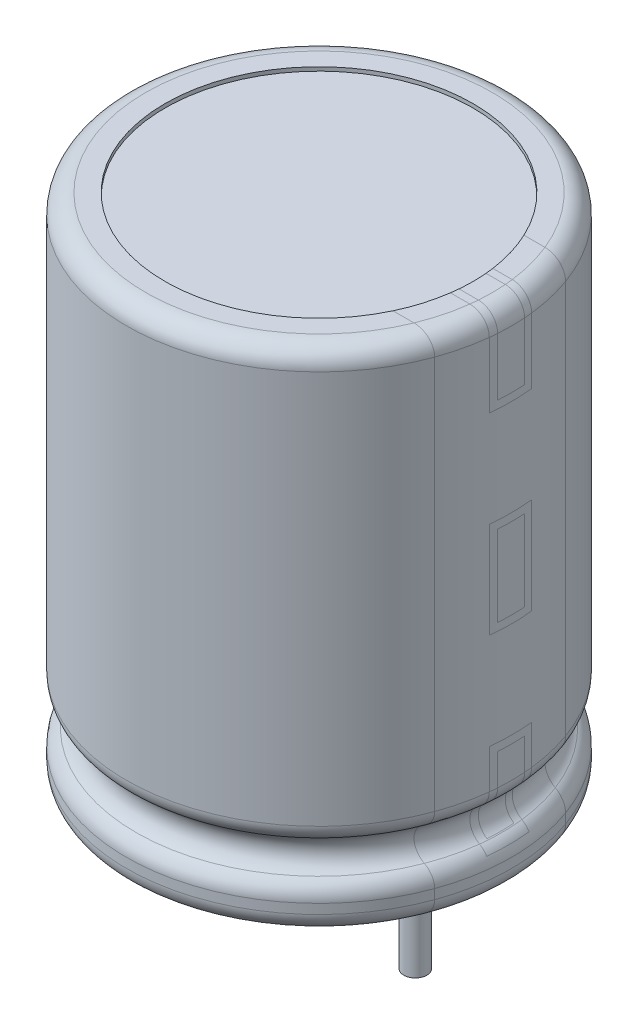
SolidWorks part; units mm, degrees
ref_plane "Front Plane" through (0, 0, 0) normal (0, 0, 1) x (1, 0, 0)
ref_plane "Top Plane" through (0, 0, 0) normal (0, 1, 0) x (1, 0, 0)
ref_plane "Right Plane" through (0, 0, 0) normal (1, 0, 0) x (0, 0, -1)
sketch "Sketch1" plane through (0, 0, 0) normal (0, 1, 0) x (1, 0, 0)
  line L0 (-2.5, 0) -> (2.5, 0) construction
  circle A0 centre (-2.5, 0) radius 0.3
  circle A1 centre (2.5, 0) radius 0.3
  dimension "D3" = 0.6
  dimension "D1" = 5
extrude "Boss-Extrude1" add sketch "Sketch1" against normal blind 3 and the other way blind 1
sketch "Sketch3" plane through (0, 0, 0) normal (0, 0, 1) x (1, 0, 0)
  line L1 (0, 0.1) -> (0, 13.2) construction
  line L2 (5, 0.5) -> (5, 0.75)
  line L3 (0, 0.1) -> (4, 0.1)
  line L4 (4, 13.2) -> (4.5, 13.2)
  line L5 (4, 0) -> (4.5, 0)
  line L6 (0, 13.1) -> (4, 13.1)
  line L7 (5, 2.4821) -> (5, 12.7)
  line L8 (4, 13.1) -> (4, 13.2)
  line L9 (5, 2.4821) -> (5, 13.2) construction
  line L10 (4, 0) -> (4, 0.1)
  line L11 (0, 13.1) -> (5, 13.1) construction
  line L12 (0, 13.2) -> (5, 13.2) construction
  line L13 (4, 2.4821) -> (4, 13.2) construction
  line L14 (0, 0.1) -> (0, 13.1)
  line L17 (0, 0.1) -> (5, 0.1) construction
  line L18 (0, 0) -> (5, 0) construction
  arc A0 (4.75, 2.049) -> (4.75, 1.183) centre (5, 1.616) ccw
  arc A1 (5, 0.75) -> (4.75, 1.183) centre (4.5, 0.75) ccw
  arc A2 (5, 2.4821) -> (4.75, 2.049) centre (4.5, 2.4821) cw
  arc A3 (5, 12.7) -> (4.5, 13.2) centre (4.5, 12.7) ccw
  arc A4 (4.5, 0) -> (5, 0.5) centre (4.5, 0.5) ccw
  point P1 (0, 0)
  point P2 (0, 0)
  point P13 (5, 2.116)
  point P29 (4.9638, 1.6359)
  point P30 (0, 0)
  point P32 (4.5, 1.616)
  dimension "D2" = 1
  dimension "D1" = 0.5
  dimension "D9" = 0.5
  dimension "D3" = 13
  dimension "D6" = 10
  dimension "D7" = 0.1
  dimension "D8" = 8
  dimension "D10" = 0.25
  dimension "D4" = 9
  dimension "D5" = 1
revolve "Revolve1" add sketch "Sketch3" angle 360 about L14
sketch "Sketch4" plane through (0, 0, 0) normal (1, 0, 0) x (0, 0, -1)
  line L0 (-4.5, 0) -> (4.5, 0) construction
  line L1 (-1.7, 0) -> (1.7, 0)
  line L2 (0, 0) -> (0, 13.2) construction
  line L3 (-1.7, 13.2) -> (1.7, 13.2)
  line L4 (1.7, 0) -> (1.7, 13.2)
  line L5 (4, 13.2) -> (-4, 13.2) construction
  line L6 (-1.7, 0) -> (-1.7, 13.2)
  line L7 (-0.35, 13.3) -> (-0.35, 11.2)
  line L8 (-0.35, 13.3) -> (0.35, 13.3)
  line L9 (0, 13.3) -> (0, 11.2) construction
  line L10 (-0.35, 11.2) -> (0.35, 11.2)
  line L11 (0.35, 13.3) -> (0.35, 11.2)
  line L12 (0.55, 13.5) -> (0.55, 11)
  line L13 (-0.55, 11) -> (0.55, 11)
  line L14 (-0.55, 13.5) -> (-0.55, 11)
  line L15 (-0.55, 13.5) -> (0.55, 13.5)
  line L16 (0, 0) -> (0, -3.7489) construction
  line L17 (-0.35, 8.3) -> (-0.35, 6.2)
  line L18 (-0.35, 8.3) -> (0.35, 8.3)
  line L19 (-0.35, 6.2) -> (0.35, 6.2)
  line L20 (0.35, 8.3) -> (0.35, 6.2)
  line L21 (0.55, 8.5) -> (0.55, 6)
  line L22 (-0.55, 6) -> (0.55, 6)
  line L23 (-0.55, 8.5) -> (-0.55, 6)
  line L24 (-0.55, 8.5) -> (0.55, 8.5)
  line L25 (0, 8.3) -> (0, 6.2) construction
  line L26 (-0.35, 3.3) -> (-0.35, 1.2)
  line L27 (-0.35, 3.3) -> (0.35, 3.3)
  line L28 (-0.35, 1.2) -> (0.35, 1.2)
  line L29 (0.35, 3.3) -> (0.35, 1.2)
  line L30 (0.55, 3.5) -> (0.55, 1)
  line L31 (-0.55, 1) -> (0.55, 1)
  line L32 (-0.55, 3.5) -> (-0.55, 1)
  line L33 (-0.55, 3.5) -> (0.55, 3.5)
  line L34 (0, 3.3) -> (0, 1.2) construction
  line L35 (-0.55, 18.5) -> (0.55, 18.5)
  line L36 (-0.55, 18.5) -> (-0.55, 16)
  line L37 (-0.35, 18.3) -> (0.35, 18.3)
  line L38 (0.35, 18.3) -> (0.35, 16.2)
  line L39 (0.55, 18.5) -> (0.55, 16)
  line L40 (-0.35, 18.3) -> (-0.35, 16.2)
  line L41 (-0.35, 16.2) -> (0.35, 16.2)
  line L42 (-0.55, 16) -> (0.55, 16)
  line L51 (-0.55, 11) -> (-0.55, 8.5) construction
  line L52 (-0.55, 13.5) -> (-0.55, 16) construction
  point P64 (0, 18.3)
  dimension "D5" = 3.4
  dimension "D6" = 0.2
  dimension "D7" = 1.1
  dimension "D8" = 2.1
  dimension "D1" = 0.7
  dimension "D9" = 1
  dimension "D10" = 2.5
  dimension "D2" = 3
  dimension "D3" = 2
split line "Split Line1"
